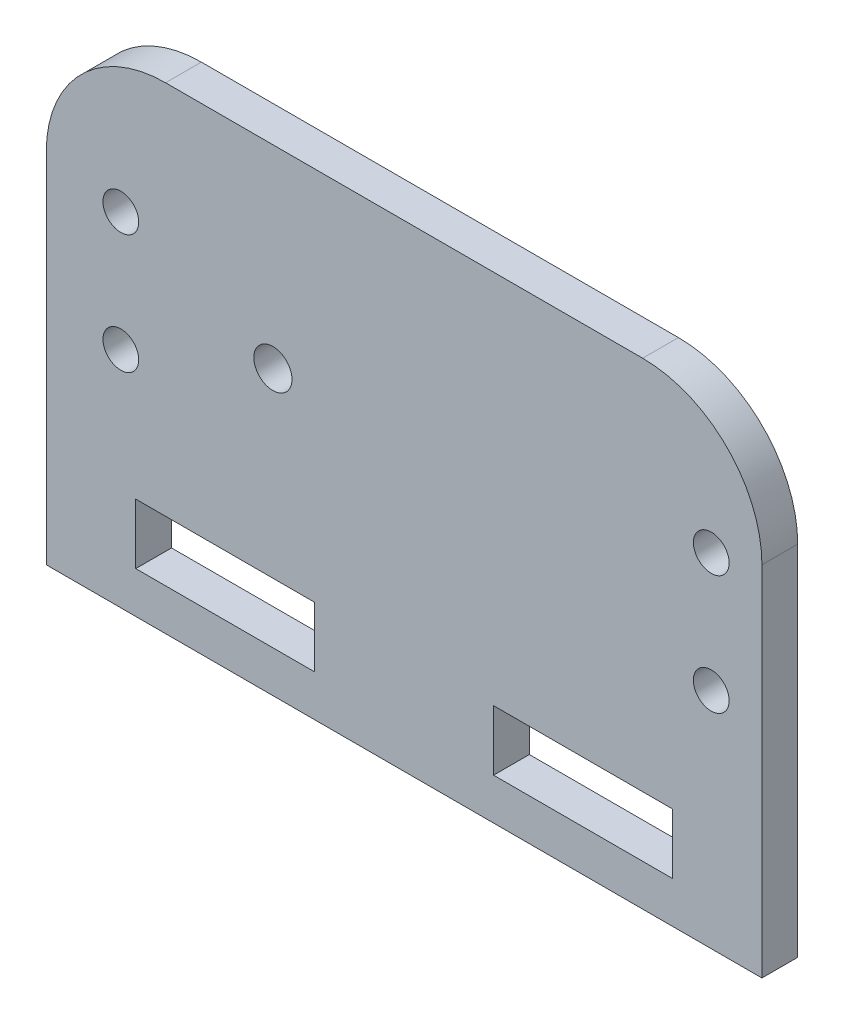
SolidWorks part; units mm, degrees
ref_plane "Plan de face" through (0, 0, 0) normal (0, 0, 1) x (1, 0, 0)
ref_plane "Plan de dessus" through (0, 0, 0) normal (0, 1, 0) x (1, 0, 0)
ref_plane "Plan de droite" through (0, 0, 0) normal (1, 0, 0) x (0, 0, -1)
sketch "Esquisse1" plane through (0, 0, 0) normal (0, 0, 1) x (1, 0, 0)
  line L0 (0, 14.9089) -> (0, -14.9089) construction
  line L1 (-20, 20) -> (20, 20)
  line L2 (-30, 10) -> (-30, -20)
  line L3 (-30, -20) -> (30, -20)
  line L4 (30, 10) -> (30, -20)
  line L5 (-30, 20) -> (30, -20) construction
  line L6 (-30, -20) -> (30, 20) construction
  line L7 (22.5, -16.525) -> (7.5, -16.525)
  line L8 (-22.5, -11.475) -> (-7.5, -11.475)
  line L9 (-22.5, -11.475) -> (-22.5, -16.525)
  line L10 (-22.5, -16.525) -> (-7.5, -16.525)
  line L11 (-7.5, -11.475) -> (-7.5, -16.525)
  line L12 (-22.5, -11.475) -> (-7.5, -16.525) construction
  line L13 (-22.5, -16.525) -> (-7.5, -11.475) construction
  line L14 (7.5, -11.475) -> (7.5, -16.525)
  line L15 (22.5, -11.475) -> (7.5, -11.475)
  line L16 (22.5, -11.475) -> (22.5, -16.525)
  arc A0 (20, 20) -> (30, 10) centre (20, 10) cw
  arc A1 (-20, 20) -> (-30, 10) centre (-20, 10) ccw
  point P0 (0, 0)
  point P9 (0, 0)
  point P10 (-15, -14)
  dimension "D7" = 10
  dimension "D1" = 60
  dimension "D2" = 40
  dimension "D3" = 6
  dimension "D4" = 5.05
  dimension "D5" = 15
  dimension "D6" = 15
extrude "Boss.-Extru.1" add sketch "Esquisse1" along normal blind 3
sketch "Esquisse2" plane through (0, 0, 3) normal (0, 0, 1) x (1, 0, 0)
  circle A0 centre (11, -35.2822) radius 7.5
  circle A1 centre (-11, 3.7532) radius 1.6
  dimension "D1" = 15
  dimension "D2" = 3.2
extrude "Enlèv. mat.-Extru.1" cut sketch "Esquisse2" against normal through all
sketch "Esquisse3" plane through (0, 0, 0) normal (0, 0, -1) x (-1, 0, 0)
  circle A0 centre (-25.75, 8.7532) radius 1.5
  circle A1 centre (-25.75, -1.2468) radius 1.5
  circle A2 centre (23.75, 8.7532) radius 1.5
  circle A3 centre (23.75, -1.2468) radius 1.5
extrude "Enlèv. mat.-Extru.2" cut sketch "Esquisse3" against normal through all
